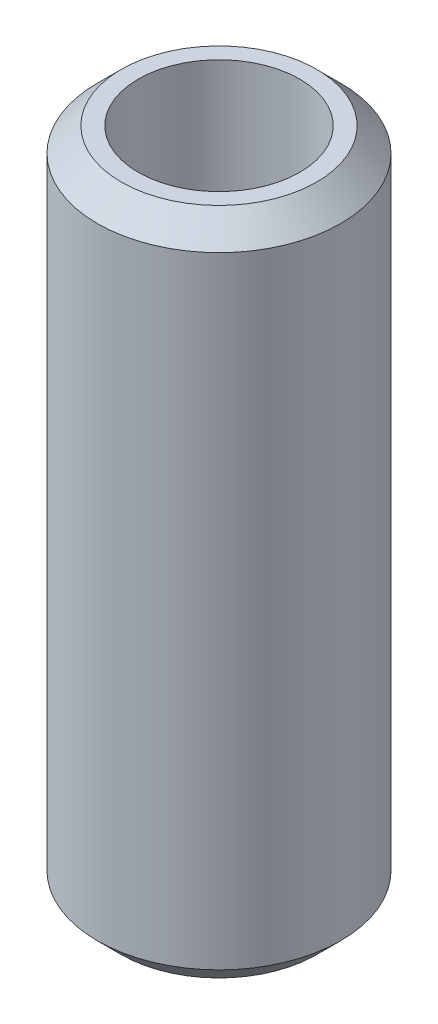
SolidWorks part; units mm, degrees
ref_plane "Front Plane" through (0, 0, 0) normal (0, 0, 1) x (1, 0, 0)
ref_plane "Top Plane" through (0, 0, 0) normal (0, 1, 0) x (1, 0, 0)
ref_plane "Right Plane" through (0, 0, 0) normal (1, 0, 0) x (0, 0, -1)
sketch "Sketch2" plane through (0, 0, 0) normal (0, 1, 0) x (1, 0, 0)
  circle A0 centre (0, 0) radius 8.434
  circle A1 centre (0, 0) radius 12.7
  dimension "D1" = 25.4
  dimension "D2" = 16.868
extrude "Boss-Extrude1" add sketch "Sketch2" along normal mid plane 69.85
chamfer "Chamfer1" distance 2.5 angle 45 2 edges at (0, -34.925, 12.7) (0, 34.925, 12.7)
